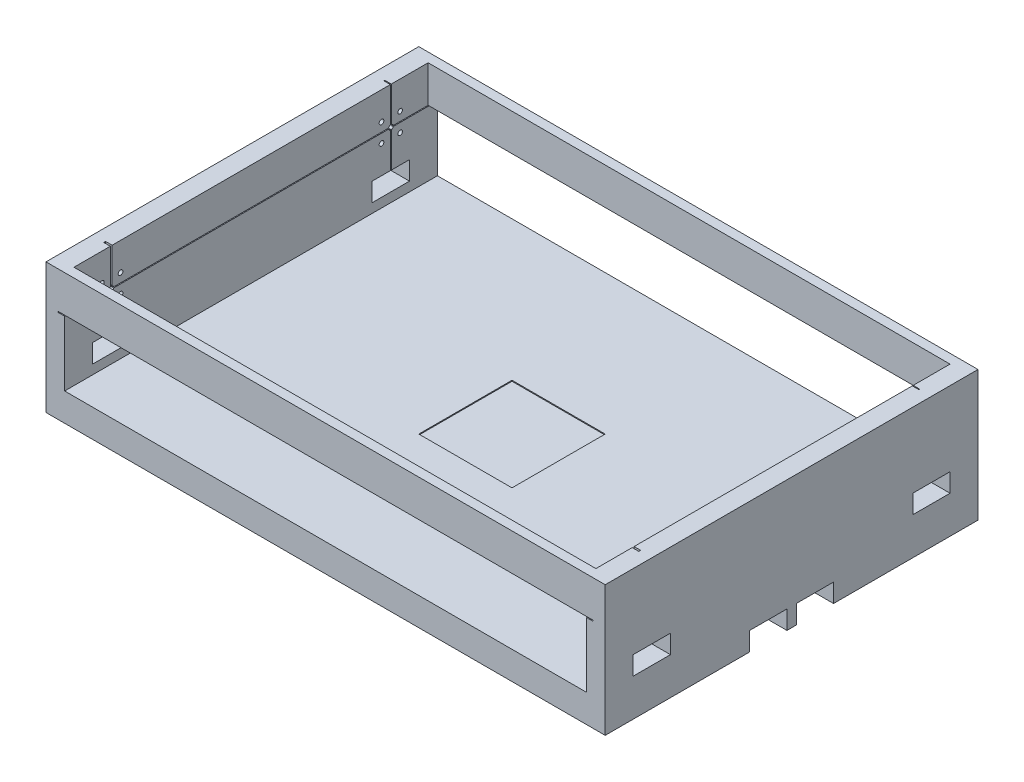
SolidWorks part; units mm, degrees
material "ABS"
ref_plane "前视基准面" through (0, 0, 0) normal (0, 0, 1) x (1, 0, 0)
ref_plane "上视基准面" through (0, 0, 0) normal (0, 1, 0) x (1, 0, 0)
ref_plane "右视基准面" through (0, 0, 0) normal (1, 0, 0) x (0, 0, -1)
sketch "base" plane through (0, 0, 0) normal (0, 1, 0) x (1, 0, 0)
  line L1 (0, 0) -> (600, 0)
  line L2 (0, 0) -> (0, -400)
  line L3 (0, -400) -> (600, -400)
  line L4 (600, 0) -> (600, -400)
  dimension "D1" = 600
  dimension "D2" = 400
  dimension "D3" = 0
extrude "凸台-拉伸1" add sketch "base" along normal blind 120 contours L1 L4 L3 L2
sketch "草图5" plane through (0, 0, 0) normal (0, -1, 0) x (1, 0, 0)
  line L0 (0, 0) -> (0, 400) construction
  line L5 (0, 155) -> (600, 155)
  line L6 (0, 155) -> (0, 145)
  line L7 (0, 145) -> (600, 145)
  line L8 (600, 155) -> (600, 145)
  line L9 (0, 105) -> (600, 105)
  line L10 (0, 105) -> (0, 95)
  line L11 (0, 95) -> (600, 95)
  line L12 (600, 105) -> (600, 95)
  line L13 (0, 5) -> (600, 5)
  line L14 (0, 5) -> (0, 0)
  line L15 (0, 0) -> (600, 0)
  line L16 (600, 5) -> (600, 0)
  line L17 (0, 55) -> (600, 55)
  line L18 (0, 55) -> (0, 45)
  line L19 (0, 45) -> (600, 45)
  line L20 (600, 55) -> (600, 45)
  line L21 (600, 0) -> (600, 400) construction
  line L22 (0, 255) -> (600, 255)
  line L23 (0, 255) -> (0, 245)
  line L24 (0, 245) -> (600, 245)
  line L25 (600, 255) -> (600, 245)
  line L26 (0, 205) -> (600, 205)
  line L27 (0, 205) -> (0, 195)
  line L28 (0, 195) -> (600, 195)
  line L29 (600, 205) -> (600, 195)
  line L30 (0, 305) -> (600, 305)
  line L31 (0, 305) -> (0, 295)
  line L32 (0, 295) -> (600, 295)
  line L33 (600, 305) -> (600, 295)
  line L35 (0, 355) -> (600, 355)
  line L36 (0, 355) -> (0, 345)
  line L37 (0, 345) -> (600, 345)
  line L38 (600, 355) -> (600, 345)
  line L49 (0, 400) -> (600, 400)
  line L50 (0, 400) -> (0, 395)
  line L51 (0, 395) -> (600, 395)
  line L52 (600, 400) -> (600, 395)
  dimension "D3" = 0
  dimension "D4" = 0
  dimension "D5" = 5
  dimension "D6" = 10
  dimension "D7" = 0
  dimension "D8" = 10
  dimension "D9" = 0
  dimension "D10" = 0
  dimension "D11" = 0
  dimension "D12" = 0
  dimension "D13" = 10
  dimension "D14" = 10
  dimension "D15" = 5
  dimension "D16" = 40
  dimension "D17" = 40
  dimension "D18" = 40
  dimension "D19" = 40
  dimension "D20" = 10
  dimension "D21" = 40
  dimension "D22" = 40
  dimension "D23" = 40
  dimension "D24" = 10
  dimension "D26" = 10
extrude "凸台-拉伸4" add sketch "草图5" along normal blind 20
sketch "草图6" plane through (0, 0, 0) normal (0, -1, 0) x (1, 0, 0)
  line L0 (0, 245) -> (600, 245) construction
  line L1 (30, 400) -> (0, 400)
  line L2 (30, 400) -> (30, 245)
  line L3 (30, 245) -> (0, 245)
  line L4 (0, 400) -> (0, 245)
  line L5 (30, 155) -> (0, 155)
  line L6 (30, 155) -> (30, 0)
  line L7 (30, 0) -> (0, 0)
  line L8 (0, 155) -> (0, 0)
  line L9 (0, 0) -> (600, 0) construction
  line L10 (0, 245) -> (600, 245) construction
  line L11 (570, 400) -> (600, 400)
  line L12 (570, 400) -> (570, 245)
  line L13 (570, 245) -> (600, 245)
  line L14 (600, 400) -> (600, 245)
  line L15 (600, 155) -> (570, 155)
  line L16 (600, 155) -> (600, 0)
  line L17 (600, 0) -> (570, 0)
  line L18 (570, 155) -> (570, 0)
  line L19 (0, 355) -> (0, 395) construction
  line L20 (0, 400) -> (0, 395) construction
  dimension "D2" = 30
  dimension "D3" = 30
  dimension "D4" = 30
extrude "凸台-拉伸5" add sketch "草图6" along normal blind 20
sketch "草图7" plane through (0, 0, 400) normal (0, 0, 1) x (1, 0, 0)
  line L0 (0, 120) -> (600, 120) construction
  line L1 (20, 120) -> (580, 120)
  line L2 (20, 120) -> (20, 10)
  line L3 (20, 10) -> (580, 10)
  line L4 (580, 120) -> (580, 10)
  dimension "D1" = 20
  dimension "D2" = 20
  dimension "D3" = 30
extrude "切除-拉伸1" cut sketch "草图7" against normal through all contours L2 L3 L4 L1
sketch "草图8" plane through (20, 0, 0) normal (1, 0, 0) x (0, 0, -1)
  circle A0 centre (-360, 90) radius 2.5
  circle A1 centre (-60, 90) radius 2.5
  circle A2 centre (-340, 70) radius 2.5
  circle A3 centre (-360, 70) radius 2.5
  circle A4 centre (-340, 90) radius 2.5
  circle A5 centre (-60, 70) radius 2.5
  circle A6 centre (-40, 70) radius 2.5
  circle A7 centre (-40, 90) radius 2.5
  circle A8 centre (-350, 80) radius 2.5
  circle A9 centre (-50, 80) radius 2.5
  dimension "D4" = 5
  dimension "D5" = 5
  dimension "D6" = 5
  dimension "D7" = 5
  dimension "D3" = 5
  dimension "D8" = 5
  dimension "D9" = 5
  dimension "D10" = 5
  dimension "D15" = 5
  dimension "D16" = 5
  dimension "D1" = 60
  dimension "D2" = 80
  dimension "D11" = 40
  dimension "D12" = 20
  dimension "D13" = 280
  dimension "D14" = 20
  dimension "D17" = 10
  dimension "D18" = 10
  dimension "D19" = 300
extrude "切除-拉伸2" cut sketch "草图8" along normal blind 565 and the other way blind 5
sketch "草图9" plane through (20, 0, 0) normal (1, 0, 0) x (0, 0, -1)
  line L0 (0, 10) -> (-400, 10) construction
  line L1 (-370, 40) -> (-330, 40)
  line L2 (-370, 40) -> (-370, 20)
  line L3 (-370, 20) -> (-330, 20)
  line L4 (-330, 40) -> (-330, 20)
  line L5 (-70, 40) -> (-30, 40)
  line L6 (-70, 40) -> (-70, 20)
  line L7 (-70, 20) -> (-30, 20)
  line L8 (-30, 40) -> (-30, 20)
  dimension "D1" = 40
  dimension "D2" = 20
  dimension "D3" = 30
  dimension "D4" = 40
  dimension "D5" = 30
  dimension "D6" = 10
extrude "切除-拉伸3" cut sketch "草图9" against normal through all and the other way through all
sketch "草图10" plane through (0, 10, 0) normal (0, 1, 0) x (1, 0, 0)
  line L1 (250, -150) -> (350, -150)
  line L2 (250, -150) -> (250, -250)
  line L3 (250, -250) -> (350, -250)
  line L4 (350, -150) -> (350, -250)
  dimension "D1" = 230
  dimension "D2" = 230
  dimension "D3" = 150
  dimension "D4" = 150
extrude "切除-拉伸4" cut sketch "草图10" against normal blind 1
sketch "草图11" plane through (580, 0, 0) normal (-1, 0, 0) x (0, 0, 1)
  line L1 (0, 80.5) -> (400, 80.5)
  line L2 (0, 80.5) -> (0, 79.5)
  line L3 (0, 79.5) -> (400, 79.5)
  line L4 (400, 80.5) -> (400, 79.5)
  point P4 (0, 80)
  dimension "D1" = 1
  dimension "D2" = 70
extrude "切除-拉伸5" cut sketch "草图11" against normal blind 7 and the other way blind 567 contours L3 L4 L1 L2
sketch "草图13" plane through (580, 0, 0) normal (-1, 0, 0) x (0, 0, 1)
  line L0 (0, 120) -> (400, 120) construction
  line L1 (49.5, 120) -> (50.5, 120)
  line L2 (49.5, 120) -> (49.5, 40)
  line L3 (49.5, 40) -> (50.5, 40)
  line L4 (50.5, 120) -> (50.5, 40)
  line L5 (349, 120) -> (351, 120)
  line L6 (349, 120) -> (349, 40)
  line L7 (349, 40) -> (351, 40)
  line L8 (351, 120) -> (351, 40)
  line L9 (70, 40) -> (30, 40) construction
  line L10 (370, 40) -> (330, 40) construction
  point P8 (50, 120)
  point P16 (350, 120)
  dimension "D1" = 50
  dimension "D2" = 50
  dimension "D3" = 2
  dimension "D4" = 1
extrude "切除-拉伸7" cut sketch "草图13" against normal blind 7 and the other way blind 567
sketch "草图15" plane through (20, 0, 0) normal (1, 0, 0) x (0, 0, -1)
  line L0 (-47.5505, 80.5) -> (0, 80.5) construction
  line L1 (-400, 120) -> (-390, 120)
  line L2 (-400, 120) -> (-400, 80.5)
  line L3 (-400, 80.5) -> (-390, 80.5)
  line L4 (-390, 120) -> (-390, 80.5)
  line L5 (-10, 120) -> (0, 120)
  line L6 (-10, 120) -> (-10, 80.5)
  line L7 (-10, 80.5) -> (0, 80.5)
  line L8 (0, 120) -> (0, 80.5)
  dimension "D1" = 10
  dimension "D2" = 10
extrude "凸台-拉伸7" add sketch "草图15" along normal blind 561
